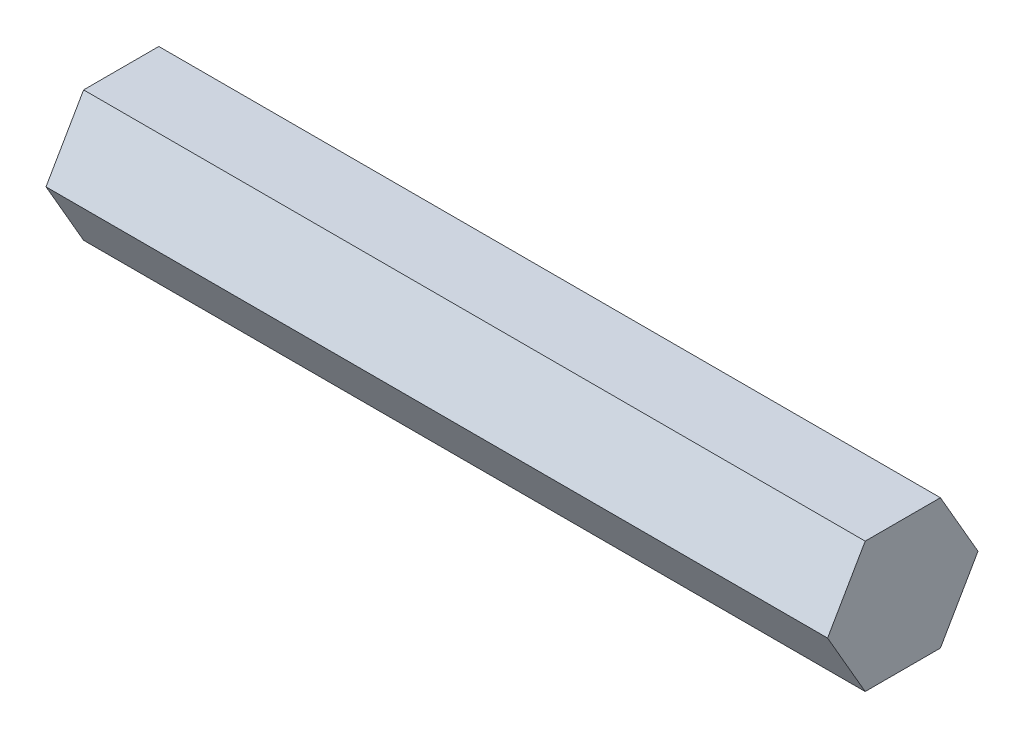
SolidWorks part; units mm, degrees
material "6061-T6 (SS)"
ref_plane "Front Plane" through (0, 0, 0) normal (0, 0, 1) x (1, 0, 0)
ref_plane "Top Plane" through (0, 0, 0) normal (0, 1, 0) x (1, 0, 0)
ref_plane "Right Plane" through (0, 0, 0) normal (1, 0, 0) x (0, 0, -1)
sketch "Sketch1" plane through (0, 0, 0) normal (1, 0, 0) x (0, 0, -1)
  line L1 (-7.3323, 0) -> (-3.6662, -6.35)
  line L2 (-3.6662, -6.35) -> (3.6662, -6.35)
  line L3 (3.6662, -6.35) -> (7.3323, 0)
  line L4 (7.3323, 0) -> (3.6662, 6.35)
  line L5 (3.6662, 6.35) -> (-3.6662, 6.35)
  line L6 (-3.6662, 6.35) -> (-7.3323, 0)
  circle A0 centre (0, 0) radius 6.35 construction
  dimension "D1" = 12.7
extrude "Boss-Extrude1" add sketch "Sketch1" along normal blind 76.2
